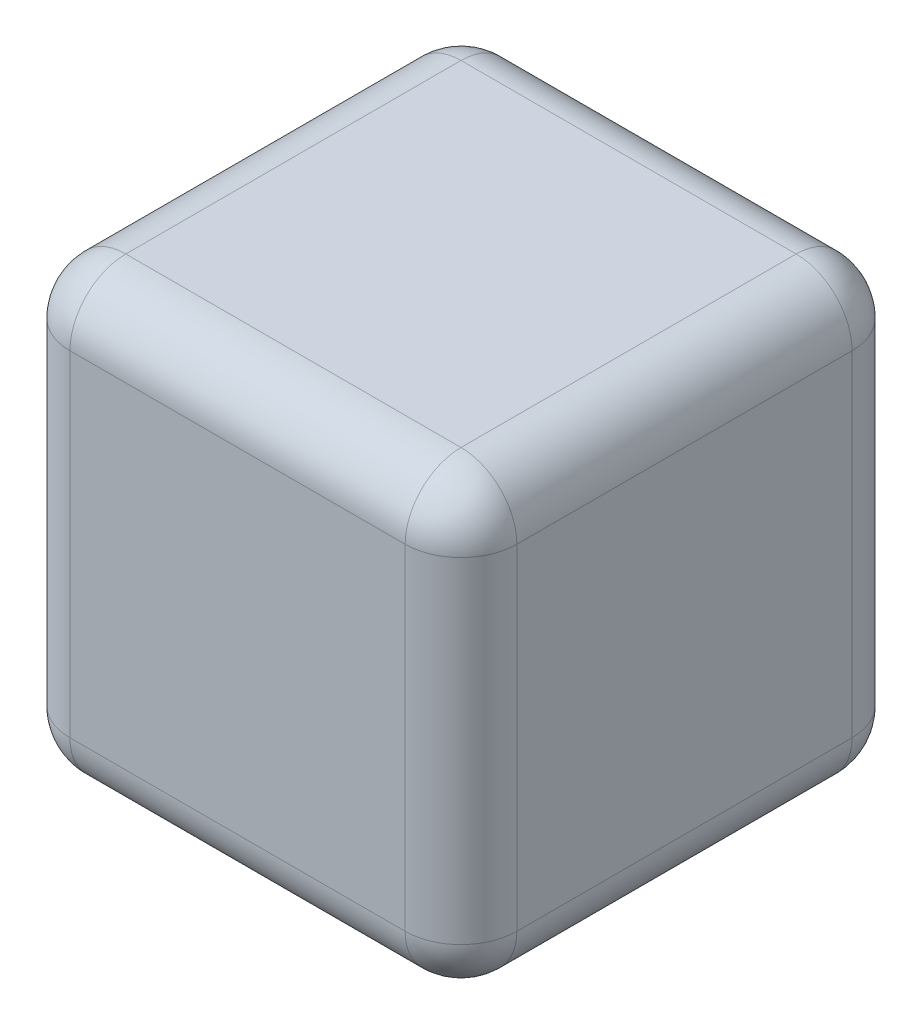
SolidWorks part; units mm, degrees
ref_plane "Front Plane" through (0, 0, 0) normal (0, 0, 1) x (1, 0, 0)
ref_plane "Top Plane" through (0, 0, 0) normal (0, 1, 0) x (1, 0, 0)
ref_plane "Right Plane" through (0, 0, 0) normal (1, 0, 0) x (0, 0, -1)
sketch "Sketch1" plane through (0, 0, 0) normal (0, 1, 0) x (1, 0, 0)
  line L1 (-40, 40) -> (40, 40)
  line L2 (-40, 40) -> (-40, -40)
  line L3 (-40, -40) -> (40, -40)
  line L4 (40, 40) -> (40, -40)
  line L5 (-40, 40) -> (40, -40) construction
  line L6 (-40, -40) -> (40, 40) construction
  dimension "D2" = 80
  dimension "D3" = 80
extrude "Boss-Extrude1" add sketch "Sketch1" along normal blind 80
sketch "Sketch2" plane through (0, 0, 0) normal (0, -1, 0) x (1, 0, 0)
  circle A0 centre (0, 0) radius 5
  dimension "D1" = 10
extrude "Boss-Extrude2" add sketch "Sketch2" along normal blind 20
fillet "Fillet1" radius 10 12 edges at (0, 80, -40) (0, 0, -40) (40, 80, 0) (40, 40, -40) (40, 0, 0) (-40, 40, -40) (-40, 80, 0) (-40, 0, 0) (-40, 40, 40) (0, 80, 40) (40, 40, 40) (0, 0, 40)
fillet "Fillet2" radius 2 1 edges at (0, -20, -5)
